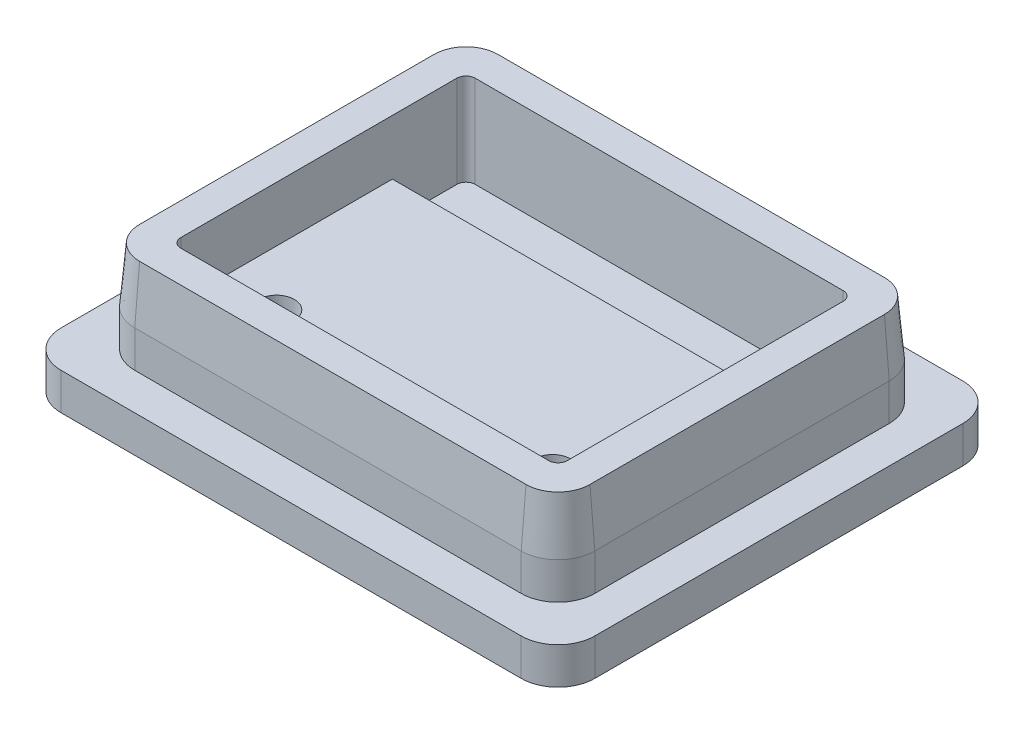
SolidWorks part; units mm, degrees
ref_plane "Front Plane" through (0, 0, 0) normal (0, 0, 1) x (1, 0, 0)
ref_plane "Top Plane" through (0, 0, 0) normal (0, 1, 0) x (1, 0, 0)
ref_plane "Right Plane" through (0, 0, 0) normal (1, 0, 0) x (0, 0, -1)
sketch "Sketch1" plane through (0, 0, 0) normal (0, 1, 0) x (1, 0, 0)
  line L5 (-14.5, -12) -> (14.5, -12)
  line L6 (-14.5, -12) -> (-14.5, 12)
  line L7 (-14.5, 12) -> (14.5, 12)
  line L8 (14.5, -12) -> (14.5, 12)
  line L9 (-14.5, -12) -> (14.5, 12) construction
  line L10 (-14.5, 12) -> (14.5, -12) construction
  point P0 (0, 0)
  dimension "D1" = 29
  dimension "D2" = 24
extrude "Boss-Extrude1" add sketch "Sketch1" along normal blind 2
sketch "Sketch2" plane through (0, 2, 0) normal (0, 1, 0) x (1, 0, 0)
  line L0 (-12.5, 10) -> (12.5, 10)
  line L1 (-10.5, -8) -> (10.5, -8)
  line L2 (-10.5, -8) -> (-10.5, 8)
  line L3 (-10.5, 8) -> (10.5, 8)
  line L4 (10.5, -8) -> (10.5, 8)
  line L5 (-10.5, -8) -> (10.5, 8) construction
  line L6 (-10.5, 8) -> (10.5, -8) construction
  line L7 (12.5, -10) -> (12.5, 10)
  line L8 (-12.5, -10) -> (12.5, -10)
  line L9 (-12.5, -10) -> (-12.5, 10)
  point P0 (0, 0)
  dimension "D1" = 16
  dimension "D2" = 21
  dimension "D3" = 2
extrude "Boss-Extrude2" add sketch "Sketch2" along normal blind 5
sketch "Sketch3" plane through (0, 2, 0) normal (0, 1, 0) x (1, 0, 0)
  line L0 (-10.5, -5.3) -> (10.5, -5.3) construction
  line L1 (-10.5, 8) -> (-10.5, -8) construction
  line L2 (10.5, -8) -> (10.5, 8) construction
  line L3 (-10.5, -8) -> (10.5, -8) construction
  line L5 (-7.5, -8) -> (-7.5, 8) construction
  line L6 (-10.5, -8) -> (10.5, -8) construction
  line L7 (10.5, 8) -> (-10.5, 8) construction
  line L9 (-10.5, 8) -> (-10.5, -8) construction
  line L10 (-10.5, 4) -> (10.5, 4)
  line L11 (10.5, -8) -> (10.5, 8) construction
  line L12 (10.5, 8) -> (-10.5, 8) construction
  line L13 (-10.5, 4) -> (-10.5, -8)
  line L14 (-10.5, -8) -> (10.5, -8)
  line L15 (10.5, -8) -> (10.5, 4)
  line L16 (0, -8) -> (0, 8) construction
  circle A0 centre (-7.5, -5.3) radius 0.975
  circle A2 centre (7.5, -5.3) radius 0.975
  dimension "D4" = 1.95
  dimension "D1" = 2.7
  dimension "D2" = 7.5
  dimension "D6" = 4
extrude "Boss-Extrude3" add sketch "Sketch3" along normal blind 2
fillet "Fillet1" radius 2 8 edges at (12.5, 4.5, -10) (12.5, 4.5, 10) (-12.5, 4.5, 10) (-12.5, 4.5, -10) (14.5, 1, 12) (-14.5, 1, 12) (-14.5, 1, -12) (14.5, 1, -12)
fillet "Fillet5" radius 0.5 4 edges at (-10.5, 5.5, 8) (-10.5, 4.5, -8) (10.5, 4.5, -8) (10.5, 5.5, 8)
chamfer "Chamfer1" distance 3 angle 5 8 edges at (-11.9142, 7, 9.4142) (0, 7, 10) (-12.5, 7, 0) (11.9142, 7, 9.4142) (-11.9142, 7, -9.4142) (12.5, 7, 0) (0, 7, -10) (11.9142, 7, -9.4142)
